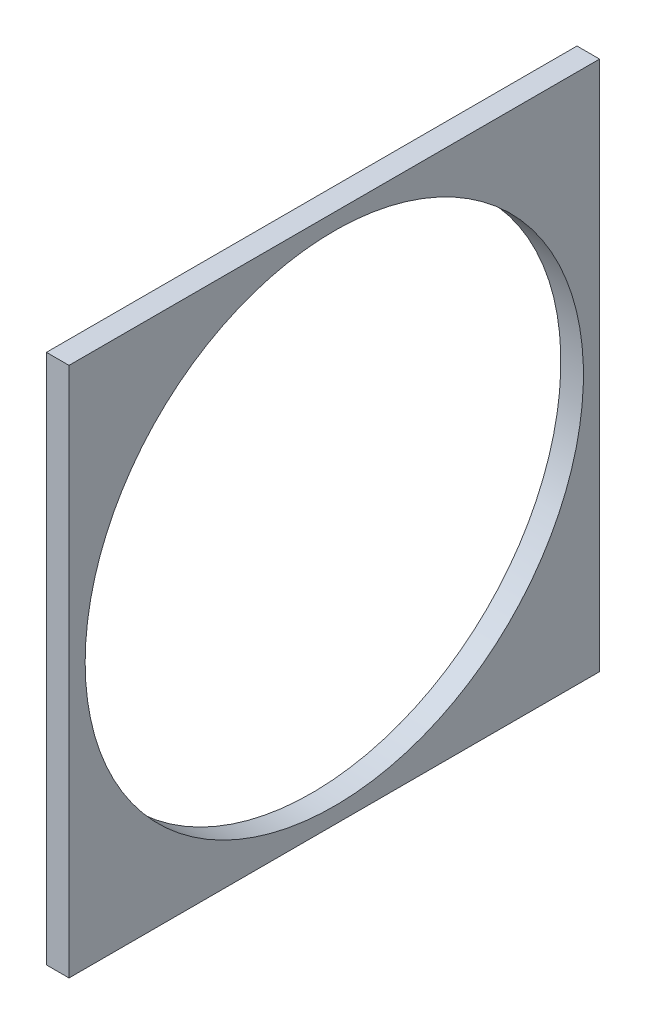
SolidWorks part; units mm, degrees
material "Beech"
ref_plane "Front Plane" through (0, 0, 0) normal (0, 0, 1) x (1, 0, 0)
ref_plane "Top Plane" through (0, 0, 0) normal (0, 1, 0) x (1, 0, 0)
ref_plane "Right Plane" through (0, 0, 0) normal (1, 0, 0) x (0, 0, -1)
sketch "Sketch1" plane through (0, 0, 0) normal (1, 0, 0) x (0, 0, -1)
  line L0 (0, 0) -> (-231.57, 0) construction
  line L1 (0, 0) -> (0, 231.57) construction
  line L2 (0, 231.57) -> (-231.57, 231.57) construction
  line L3 (-231.57, 231.57) -> (-231.57, 0) construction
  line L4 (-231.57, 0) -> (-246.57, 0) construction
  line L5 (0, 231.57) -> (0, 246.57) construction
  line L6 (0, 246.57) -> (-246.57, 246.57) construction
  line L7 (-246.57, 246.57) -> (-246.57, 0) construction
  line L9 (246.57, -246.57) -> (-246.57, -246.57)
  line L10 (246.57, -246.57) -> (246.57, 246.57)
  line L11 (246.57, 246.57) -> (-246.57, 246.57)
  line L12 (-246.57, -246.57) -> (-246.57, 246.57)
  line L13 (246.57, -246.57) -> (-246.57, 246.57) construction
  line L14 (246.57, 246.57) -> (-246.57, -246.57) construction
  circle A0 centre (0, 0) radius 231.57
  dimension "D1" = 463.14
  dimension "D2" = 15
extrude "Boss-Extrude1" add sketch "Sketch1" along normal blind 21
